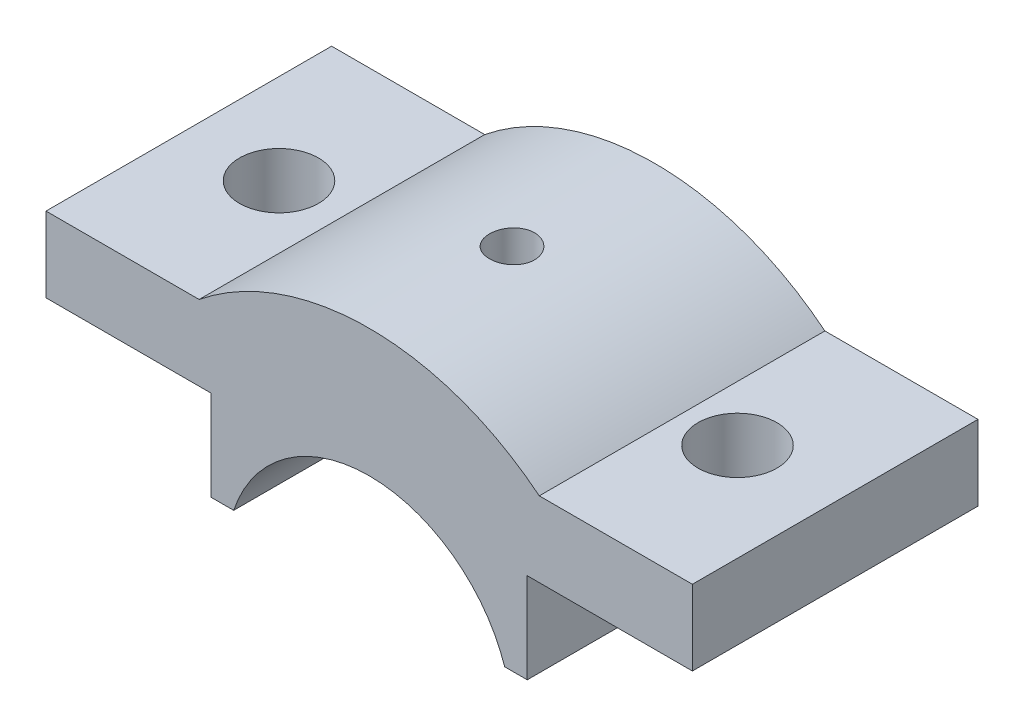
SolidWorks part; units mm, degrees
ref_plane "Front Plane" through (0, 0, 0) normal (0, 0, 1) x (1, 0, 0)
ref_plane "Top Plane" through (0, 0, 0) normal (0, 1, 0) x (1, 0, 0)
ref_plane "Right Plane" through (0, 0, 0) normal (1, 0, 0) x (0, 0, -1)
sketch "Sketch1" plane through (0, 0, 0) normal (0, 0, 1) x (1, 0, 0)
  line L0 (0, -19) -> (0, -105.2777) construction
  line L1 (0, -105.2777) -> (0, -19) construction
  line L2 (0, 0) -> (167.4949, 0) construction
  line L3 (167.4949, 0) -> (-173.9371, 0) construction
  line L4 (0, 0) -> (0, 89.681) construction
  line L5 (21.0278, 6) -> (21.0278, 18)
  line L6 (18.0278, 6) -> (21.0278, 6)
  line L7 (-18.0278, 6) -> (-21.0278, 6)
  line L8 (-21.0278, 6) -> (-21.0278, 18)
  line L9 (-22.6274, 28) -> (-43, 28)
  line L10 (22.6274, 28) -> (43, 28)
  line L11 (-43, 28) -> (-43, 18)
  line L12 (43, 28) -> (43, 18)
  line L13 (-43, 18) -> (-21.0278, 18)
  line L14 (21.0278, 18) -> (43, 18)
  arc A0 (18.0278, 6) -> (-18.0278, 6) centre (0, 0) ccw
  arc A1 (22.6274, 28) -> (-22.6274, 28) centre (0, 0) ccw
extrude "Boss-Extrude1" add sketch "Sketch1" along normal mid plane 38
sketch "Sketch2" plane through (0, 28, 0) normal (0, 1, 0) x (1, 0, 0)
  circle A0 centre (30, 0) radius 5.25
  circle A1 centre (-31, 0) radius 5.25
ref_plane "Plane1" through (0, 36, 0) normal (0, 1, 0) x (1, 0, 0)
sketch "Sketch3" plane through (0, 36, 0) normal (0, 1, 0) x (1, 0, 0)
  circle A0 centre (0, 0) radius 1.5
extrude "Cut-Extrude2" cut sketch "Sketch3" against normal blind 18
extrude "Cut-Extrude4" cut sketch "Sketch2" against normal blind 10 contours A0 | A1
sketch "Sketch4" plane through (0, 36, 0) normal (0, 1, 0) x (1, 0, 0)
  circle A0 centre (0, 0) radius 3
extrude "Cut-Extrude5" cut sketch "Sketch4" against normal blind 10
